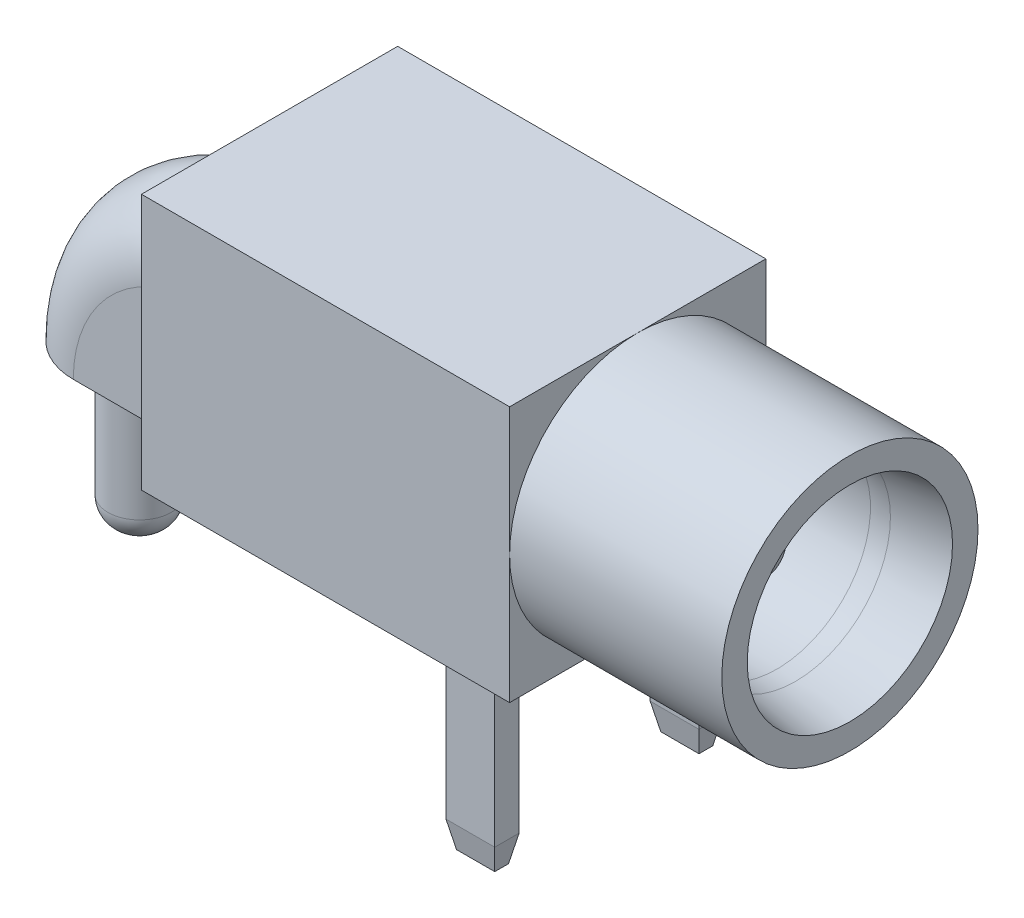
SolidWorks part; units mm, degrees
ref_plane "Front Plane" through (0, 0, 0) normal (0, 0, 1) x (1, 0, 0)
ref_plane "Top Plane" through (0, 0, 0) normal (0, 1, 0) x (1, 0, 0)
ref_plane "Right Plane" through (0, 0, 0) normal (1, 0, 0) x (0, 0, -1)
sketch "Sketch1" plane through (0, 0, 0) normal (0, 1, 0) x (1, 0, 0)
  line L1 (0, 0) -> (8.8138, 0)
  line L2 (0, 0) -> (0, 6.1341)
  line L3 (0, 6.1341) -> (8.8138, 6.1341)
  line L4 (8.8138, 0) -> (8.8138, 6.1341)
  dimension "D1" = 8.8138
  dimension "D2" = 6.1341
extrude "Boss-Extrude1" add sketch "Sketch1" along normal blind 6.1341
sketch "Sketch2" plane through (8.8138, 0, 0) normal (1, 0, 0) x (0, 0, -1)
  line L0 (6.1341, 6.1341) -> (0, 0) construction
  line L1 (0, 0) -> (6.1341, 0) construction
  line L2 (3.067, 0.8255) -> (3.0671, 0) construction
  circle A0 centre (3.0671, 3.0671) radius 3.0671
  circle A1 centre (3.0671, 3.0671) radius 2.2416
  dimension "D1" = 0.8255
extrude "Boss-Extrude2" add sketch "Sketch2" along normal blind 5.08
sketch "Sketch3" plane through (0, 0, 0) normal (-1, 0, 0) x (0, 0, 1)
  line L0 (-4.6546, 3.1115) -> (-4.6545, 0)
  line L1 (-6.1341, 0) -> (0, 0) construction
  line L2 (-4.6545, 0) -> (-1.4795, 0)
  line L3 (-1.4795, 0) -> (-1.4795, 3.1115)
  line L4 (-3.0671, 6.1341) -> (-3.0671, 4.699) construction
  line L6 (-6.1341, 6.1341) -> (0, 6.1341) construction
  arc A0 (-4.6546, 3.1115) -> (-1.4795, 3.1115) centre (-3.0671, 3.1115) cw
  point P7 (-3.067, 4.699)
  dimension "D1" = 3.175
  dimension "D2" = 1.4351
  dimension "D3" = 4.699
revolve "Revolve1" add sketch "Sketch3" angle 90 about axis through (0, 0, 0) along (0, 0, 1)
sketch "Sketch6" plane through (8.8138, 0, 0) normal (1, 0, 0) x (0, 0, -1)
  circle A0 centre (3.0671, 3.0671) radius 2.2415 construction
  circle A1 centre (3.0671, 3.0671) radius 2.2415
extrude "Cut-Extrude1" cut sketch "Sketch6" against normal offset from surface (7.0612 mm away) 1.7526 up to face at (0, 2.5098, -3.252)
sketch "Sketch11" plane through (1.7526, 0, 0) normal (1, 0, 0) x (0, 0, -1)
  circle A0 centre (3.067, 3.0671) radius 1.27
  circle A1 centre (3.0671, 3.0671) radius 2.2415 construction
  dimension "D1" = 2.54
extrude "Boss-Extrude6" add sketch "Sketch11" along normal blind 0.0254
chamfer "Chamfer3" distance 0.2159 distance2 1.524 1 edges at (13.8938, 3.0671, -5.3086)
fillet "Fillet4" radius 3.175 1 edges at (12.3698, 3.0671, -5.3086)
sketch "Sketch7" plane through (1.7526, 0, 0) normal (1, 0, 0) x (0, 0, -1)
  circle A0 centre (3.067, 3.0671) radius 0.7556
  dimension "D1" = 1.5113
extrude "Boss-Extrude3" add sketch "Sketch7" along normal offset from surface (10.2362 mm away) 1.905 separate body up to face at (13.8938, 3.0671, -5.5245)
fillet "Fillet3" radius 0.635 1 edges at (11.9888, 3.0671, -3.8227)
sketch "Sketch8" plane through (0, 0, 0) normal (0, -1, 0) x (1, 0, 0)
  circle A0 centre (-3.1115, -3.0671) radius 0.7556
  arc A1 (-3.1115, -1.4795) -> (-3.1115, -4.6546) centre (-3.1115, -3.0671) ccw construction
  dimension "D1" = 1.5113
extrude "Boss-Extrude4" add sketch "Sketch8" along normal blind 3.81 separate body
fillet "Fillet2" radius 0.635 1 edges at (-3.1115, -3.81, -3.8227)
sketch "Sketch10" plane through (0, 0, 0) normal (0, -1, 0) x (1, 0, 0)
  line L0 (8.128, -5.8039) -> (8.8138, -5.8039) construction
  line L1 (8.128, -0.3302) -> (6.9596, -0.3302)
  line L2 (8.128, -0.3302) -> (8.128, -0.9144)
  line L3 (8.128, -0.9144) -> (6.9596, -0.9144)
  line L4 (6.9596, -0.3302) -> (6.9596, -0.9144)
  line L5 (8.128, -5.8039) -> (6.9596, -5.8039)
  line L6 (8.128, -5.8039) -> (8.128, -5.2197)
  line L7 (8.128, -5.2197) -> (6.9596, -5.2197)
  line L8 (6.9596, -5.8039) -> (6.9596, -5.2197)
  line L9 (8.128, -5.8039) -> (8.128, -6.1341) construction
  line L10 (8.128, -0.3302) -> (8.8138, -0.3302) construction
  line L11 (8.128, -0.3302) -> (8.128, 0) construction
  line L13 (0, 0) -> (8.8138, 0) construction
  line L14 (8.8138, -3.0671) -> (8.8138, -6.1341) construction
  line L15 (8.8138, -6.1341) -> (0, -6.1341) construction
  line L16 (8.8138, 0) -> (8.8138, -3.0671) construction
  circle A0 centre (-3.1115, -3.0671) radius 0.7557 construction
  dimension "D5" = 10.0711
  dimension "D1" = 0.6858
  dimension "D2" = 1.1684
  dimension "D3" = 0.5842
  dimension "D4" = 0.3302
extrude "Boss-Extrude5" add sketch "Sketch10" along normal blind 4.1402 separate body
chamfer "Chamfer1" distance 0.635 distance2 0.127 4 edges at (7.5438, -4.1402, -0.9144) (6.9596, -4.1402, -0.6223) (7.5438, -4.1402, -0.3302) (8.128, -4.1402, -0.6223)
chamfer "Chamfer2" distance 0.635 distance2 0.127 4 edges at (7.5438, -4.1402, -5.8039) (6.9596, -4.1402, -5.5118) (7.5438, -4.1402, -5.2197) (8.128, -4.1402, -5.5118)
sketch "Sketch12" plane through (0, 0, 0) normal (0, -1, 0) x (1, 0, 0)
  line L0 (7.5438, -0.9144) -> (7.5438, -5.2197)
  line L1 (6.9596, -0.9144) -> (8.128, -0.9144) construction
  line L2 (8.128, -5.2197) -> (6.9596, -5.2197) construction
  point P6 (7.5438, -3.0671)
ref_point "EAGLEREF"
